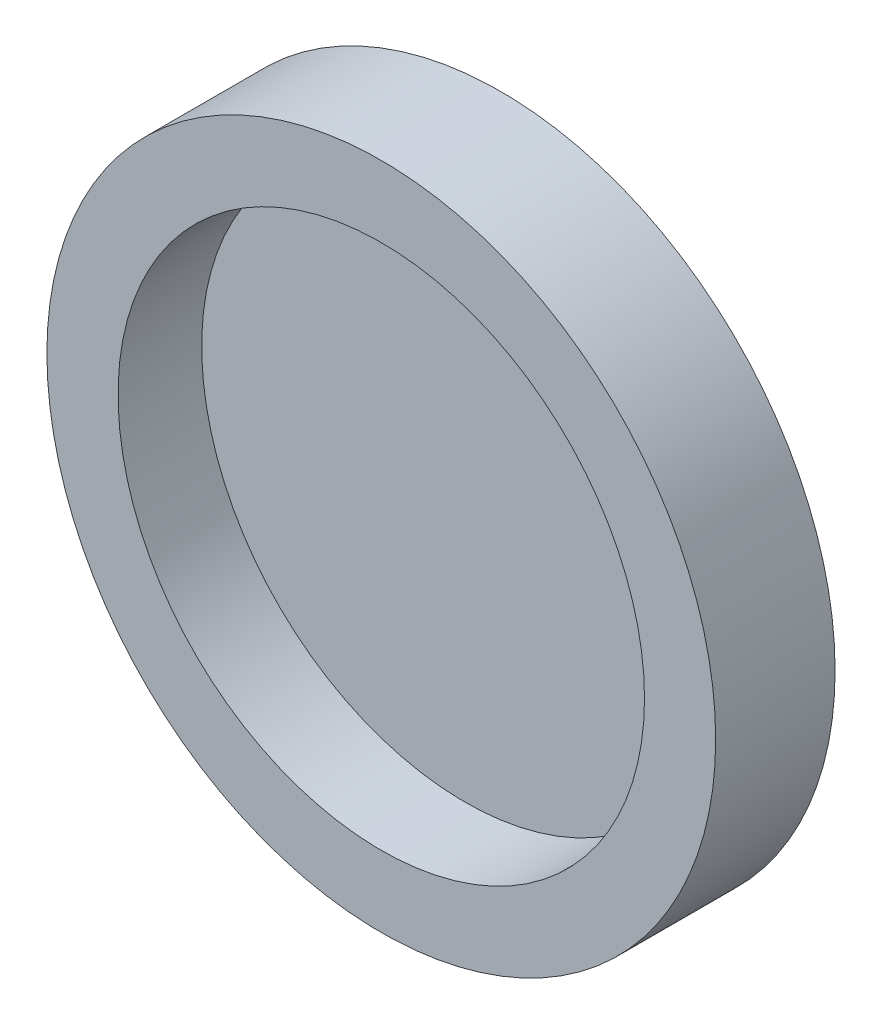
SolidWorks part; units mm, degrees
ref_plane "前视基准面" through (0, 0, 0) normal (0, 0, 1) x (1, 0, 0)
ref_plane "上视基准面" through (0, 0, 0) normal (0, 1, 0) x (1, 0, 0)
ref_plane "右视基准面" through (0, 0, 0) normal (1, 0, 0) x (0, 0, -1)
other "Configuration Table"
sketch "草图1" plane through (0, 0, 0) normal (0, 0, 1) x (1, 0, 0)
  circle A0 centre (0, 0) radius 14
extrude "凸台-拉伸1" add sketch "草图1" along normal blind 5
sketch "草图2" plane through (0, 0, 5) normal (0, 0, 1) x (1, 0, 0)
  circle A0 centre (0, 0) radius 11.02
extrude "切除-拉伸1" cut sketch "草图2" against normal blind 3.5
